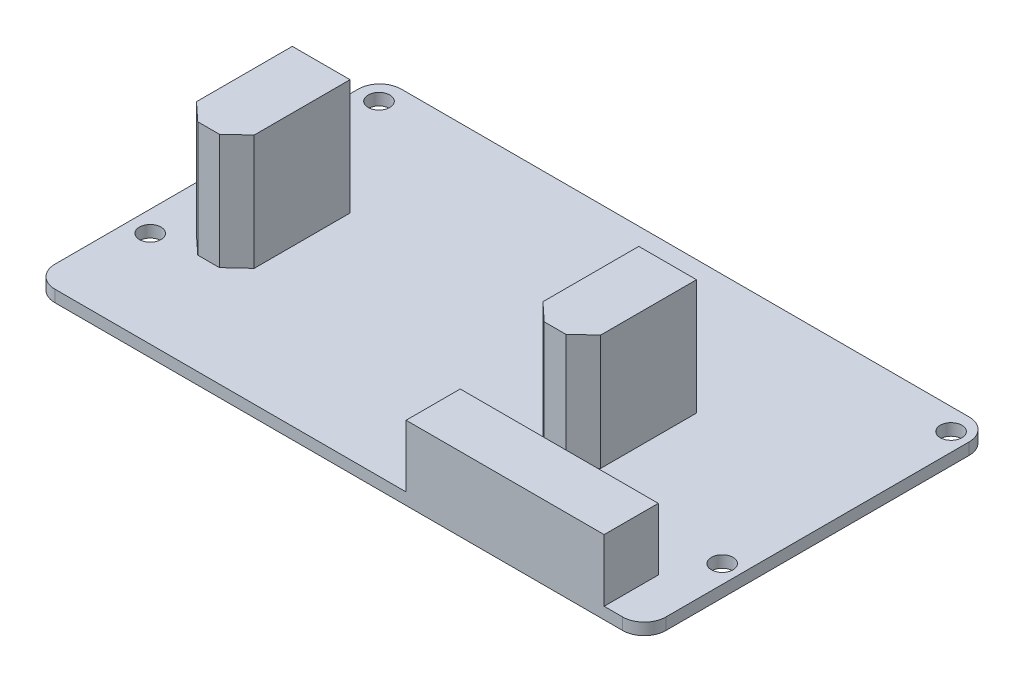
SolidWorks part; units mm, degrees
ref_plane "前视基准面" through (0, 0, 0) normal (0, 0, 1) x (1, 0, 0)
ref_plane "上视基准面" through (0, 0, 0) normal (0, 1, 0) x (1, 0, 0)
ref_plane "右视基准面" through (0, 0, 0) normal (1, 0, 0) x (0, 0, -1)
sketch "草图1" plane through (0, 0, 0) normal (0, 1, 0) x (1, 0, 0)
  line L0 (0, 0) -> (0, 48)
  line L1 (0, 48) -> (84.65, 48)
  line L2 (84.65, 48) -> (84.65, 0)
  line L3 (84.65, 0) -> (0, 0)
  line L4 (4.696, 48) -> (4.696, 43.5) construction
  line L5 (0, 43.5) -> (4.4, 43.5) construction
  line L6 (3.5906, 0) -> (3.5906, 14.8) construction
  line L7 (4.4, 43.5) -> (4.4, 14.8) construction
  line L8 (2.9, 45) -> (93.7558, 45) construction
  line L9 (84.65, 42.9544) -> (80.65, 42.9544) construction
  circle A3 centre (2.9, 45) radius 1.5
  circle A5 centre (2.9, 13.3) radius 1.5
  circle A7 centre (82.15, 45) radius 1.5
  circle A9 centre (82.15, 13.3) radius 1.5
  dimension "D3" = 4.4
  dimension "D5" = 14.8
  dimension "D1" = 84.65
  dimension "D2" = 48
  dimension "D4" = 4.5
extrude "凸台-拉伸1" add sketch "草图1" along normal blind 1.63
fillet "圆角1" radius 3 4 edges at (0, 0.815, 0) (84.65, 0.815, 0) (84.65, 0.815, -48) (0, 0.815, -48)
ref_plane "基准面1" through (51.65, 0, 0) normal (1, 0, 0) x (0, 0, -1)
sketch "草图4" plane through (51.65, 0, 0) normal (1, 0, 0) x (0, 0, -1)
  line L1 (3, 1.63) -> (0, 1.63) construction
  line L2 (3, 1.63) -> (0, 1.63) construction
  line L3 (0, 1.63) -> (7.5, 1.63)
  line L4 (7.5, 1.63) -> (7.5, 10.23)
  line L5 (7.5, 10.23) -> (0, 10.23)
  line L6 (0, 10.23) -> (0, 1.63)
extrude "凸台-拉伸2" add sketch "草图4" along normal blind 27.44
sketch "草图5" plane through (0, 1.63, 0) normal (0, 1, 0) x (1, 0, 0)
  line L0 (63.9019, 48) -> (63.9019, 29.58) construction
  line L1 (81.65, 48) -> (3, 48) construction
  line L2 (84.65, 29.58) -> (62.31, 29.58) construction
  line L3 (84.65, 3) -> (84.65, 45) construction
  line L4 (62.31, 29.58) -> (62.31, 16.3)
  line L5 (62.31, 29.58) -> (54.31, 29.58)
  line L6 (54.31, 29.58) -> (54.31, 16.3)
  line L7 (58.31, 29.58) -> (58.31, 13.98) construction
  line L8 (58.31, 13.98) -> (59.81, 13.98)
  line L9 (59.81, 13.98) -> (62.31, 16.3)
  line L10 (58.31, 13.98) -> (56.81, 13.98)
  line L11 (56.81, 13.98) -> (54.31, 16.3)
  line L12 (54.31, 29.58) -> (14.31, 29.58) construction
  line L13 (10.31, 13.98) -> (8.81, 13.98)
  line L14 (10.31, 13.98) -> (11.81, 13.98)
  line L15 (6.31, 29.58) -> (6.31, 16.3)
  line L16 (14.31, 29.58) -> (6.31, 29.58)
  line L17 (8.81, 13.98) -> (6.31, 16.3)
  line L18 (11.81, 13.98) -> (14.31, 16.3)
  line L19 (14.31, 29.58) -> (14.31, 16.3)
  dimension "D1" = 18.42
  dimension "D2" = 22.34
extrude "凸台-拉伸3" add sketch "草图5" along normal blind 16
